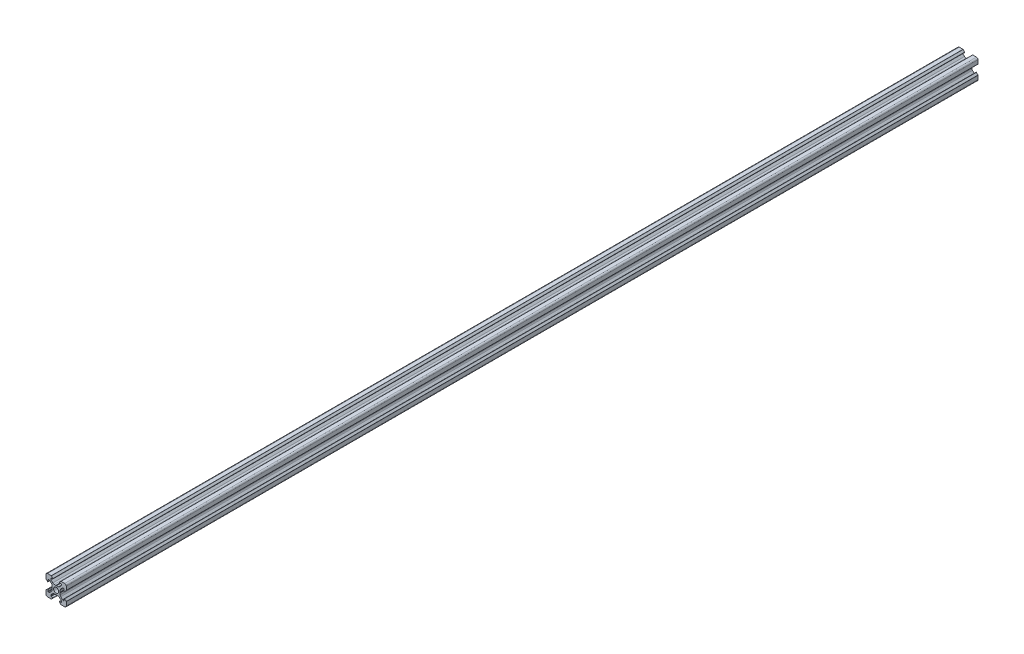
SolidWorks part; units mm, degrees
ref_plane "Спереди" through (0, 0, 0) normal (0, 0, 1) x (1, 0, 0)
ref_plane "Сверху" through (0, 0, 0) normal (0, 1, 0) x (1, 0, 0)
ref_plane "Справа" through (0, 0, 0) normal (1, 0, 0) x (0, 0, -1)
sketch "Model" plane through (0, 0, 0) normal (0, 0, 1) x (1, 0, 0)
  line L0 (18.9421, 33.3622) -> (18.9421, 34.9233)
  line L1 (18.3564, 36.3375) -> (16.6623, 38.0316)
  line L2 (15.9551, 38.3245) -> (15.1421, 38.3245)
  line L3 (14.9421, 38.1245) -> (14.9421, 36.3545)
  line L4 (13.0154, 37.6777) -> (14.5154, 36.1777)
  line L5 (12.9421, 37.8545) -> (12.9421, 41.5245)
  line L6 (18.2889, 42.9513) -> (19.7889, 41.4513)
  line L7 (22.7606, 36.9697) -> (22.9421, 36.8245)
  line L8 (23.1237, 36.9697) -> (22.9421, 36.8245)
  line L9 (23.2798, 37.0245) -> (24.8409, 37.0245)
  line L10 (26.2551, 37.6103) -> (27.9493, 39.3044)
  line L11 (28.2421, 40.0115) -> (28.2421, 40.8245)
  line L12 (28.0421, 41.0245) -> (26.2721, 41.0245)
  line L13 (27.5954, 42.9513) -> (26.0954, 41.4513)
  line L14 (27.7721, 43.0245) -> (31.4421, 43.0245)
  line L15 (32.9421, 37.8545) -> (32.9421, 41.5245)
  line L16 (32.8689, 37.6777) -> (31.3689, 36.1777)
  line L17 (30.9421, 38.1245) -> (30.9421, 36.3545)
  line L18 (29.9292, 38.3245) -> (30.7421, 38.3245)
  line L19 (27.5279, 36.3375) -> (29.222, 38.0316)
  line L20 (26.9421, 33.3622) -> (26.9421, 34.9233)
  line L21 (26.8874, 33.206) -> (26.7421, 33.0245)
  line L22 (26.8874, 32.843) -> (26.7421, 33.0245)
  line L23 (26.9421, 32.6868) -> (26.9421, 31.1257)
  line L24 (27.5279, 29.7115) -> (29.222, 28.0174)
  line L25 (29.9292, 27.7245) -> (30.7421, 27.7245)
  line L26 (30.9421, 27.9245) -> (30.9421, 29.6945)
  line L27 (32.8689, 28.3713) -> (31.3689, 29.8713)
  line L28 (32.9421, 28.1945) -> (32.9421, 24.5245)
  line L29 (27.7721, 23.0245) -> (31.4421, 23.0245)
  line L30 (27.5954, 23.0977) -> (26.0954, 24.5977)
  line L31 (28.0421, 25.0245) -> (26.2721, 25.0245)
  line L32 (28.2421, 26.0375) -> (28.2421, 25.2245)
  line L33 (26.2551, 28.4387) -> (27.9493, 26.7446)
  line L34 (23.2798, 29.0245) -> (24.8409, 29.0245)
  line L35 (23.1237, 29.0793) -> (22.9421, 29.2245)
  line L36 (22.7606, 29.0793) -> (22.9421, 29.2245)
  line L37 (19.6292, 28.4387) -> (17.935, 26.7446)
  line L38 (17.6421, 26.0375) -> (17.6421, 25.2245)
  line L39 (17.8421, 25.0245) -> (19.6121, 25.0245)
  line L40 (18.2889, 23.0977) -> (19.7889, 24.5977)
  line L41 (18.1121, 23.0245) -> (14.4421, 23.0245)
  line L42 (12.9421, 28.1945) -> (12.9421, 24.5245)
  line L43 (13.0154, 28.3713) -> (14.5154, 29.8713)
  line L44 (14.9421, 27.9245) -> (14.9421, 29.6945)
  line L45 (15.9551, 27.7245) -> (15.1421, 27.7245)
  line L46 (18.3564, 29.7115) -> (16.6623, 28.0174)
  line L47 (18.9421, 32.6868) -> (18.9421, 31.1257)
  line L48 (18.9969, 32.843) -> (19.1421, 33.0245)
  line L49 (18.9969, 33.206) -> (19.1421, 33.0245)
  line L50 (22.6045, 29.0245) -> (21.0434, 29.0245)
  line L51 (22.6045, 37.0245) -> (21.0434, 37.0245)
  line L52 (19.6292, 37.6103) -> (17.935, 39.3044)
  line L53 (17.6421, 40.0115) -> (17.6421, 40.8245)
  line L54 (17.8421, 41.0245) -> (19.6121, 41.0245)
  line L55 (18.1121, 43.0245) -> (14.4421, 43.0245)
  arc A0 (18.9421, 33.3622) -> (18.9969, 33.206) centre (19.1921, 33.3622) ccw
  arc A1 (18.9421, 34.9233) -> (18.3564, 36.3375) centre (16.9421, 34.9233) ccw
  arc A2 (16.6623, 38.0316) -> (15.9551, 38.3245) centre (15.9551, 37.3245) ccw
  arc A3 (15.1421, 38.3245) -> (14.9421, 38.1245) centre (15.1421, 38.1245) ccw
  arc A4 (14.5154, 36.1777) -> (14.9421, 36.3545) centre (14.6921, 36.3545) ccw
  arc A5 (12.9421, 37.8545) -> (13.0154, 37.6777) centre (13.1921, 37.8545) ccw
  arc A6 (14.4421, 43.0245) -> (12.9421, 41.5245) centre (14.4421, 41.5245) ccw
  arc A7 (18.2889, 42.9513) -> (18.1121, 43.0245) centre (18.1121, 42.7745) ccw
  arc A8 (19.6121, 41.0245) -> (19.7889, 41.4513) centre (19.6121, 41.2745) ccw
  arc A9 (17.8421, 41.0245) -> (17.6421, 40.8245) centre (17.8421, 40.8245) ccw
  arc A10 (17.6421, 40.0115) -> (17.935, 39.3044) centre (18.6421, 40.0115) ccw
  arc A11 (19.6292, 37.6103) -> (21.0434, 37.0245) centre (21.0434, 39.0245) ccw
  arc A12 (22.7606, 36.9697) -> (22.6045, 37.0245) centre (22.6045, 36.7745) ccw
  arc A13 (23.2798, 37.0245) -> (23.1237, 36.9697) centre (23.2798, 36.7745) ccw
  arc A14 (24.8409, 37.0245) -> (26.2551, 37.6103) centre (24.8409, 39.0245) ccw
  arc A15 (27.9493, 39.3044) -> (28.2421, 40.0115) centre (27.2421, 40.0115) ccw
  arc A16 (28.2421, 40.8245) -> (28.0421, 41.0245) centre (28.0421, 40.8245) ccw
  arc A17 (26.0954, 41.4513) -> (26.2721, 41.0245) centre (26.2721, 41.2745) ccw
  arc A18 (27.7721, 43.0245) -> (27.5954, 42.9513) centre (27.7721, 42.7745) ccw
  arc A19 (32.9421, 41.5245) -> (31.4421, 43.0245) centre (31.4421, 41.5245) ccw
  arc A20 (32.8689, 37.6777) -> (32.9421, 37.8545) centre (32.6921, 37.8545) ccw
  arc A21 (30.9421, 36.3545) -> (31.3689, 36.1777) centre (31.1921, 36.3545) ccw
  arc A22 (30.9421, 38.1245) -> (30.7421, 38.3245) centre (30.7421, 38.1245) ccw
  arc A23 (29.9292, 38.3245) -> (29.222, 38.0316) centre (29.9292, 37.3245) ccw
  arc A24 (27.5279, 36.3375) -> (26.9421, 34.9233) centre (28.9421, 34.9233) ccw
  arc A25 (26.8874, 33.206) -> (26.9421, 33.3622) centre (26.6921, 33.3622) ccw
  arc A26 (26.9421, 32.6868) -> (26.8874, 32.843) centre (26.6921, 32.6868) ccw
  arc A27 (26.9421, 31.1257) -> (27.5279, 29.7115) centre (28.9421, 31.1257) ccw
  arc A28 (29.222, 28.0174) -> (29.9292, 27.7245) centre (29.9292, 28.7245) ccw
  arc A29 (30.7421, 27.7245) -> (30.9421, 27.9245) centre (30.7421, 27.9245) ccw
  arc A30 (31.3689, 29.8713) -> (30.9421, 29.6945) centre (31.1921, 29.6945) ccw
  arc A31 (32.9421, 28.1945) -> (32.8689, 28.3713) centre (32.6921, 28.1945) ccw
  arc A32 (31.4421, 23.0245) -> (32.9421, 24.5245) centre (31.4421, 24.5245) ccw
  arc A33 (27.5954, 23.0977) -> (27.7721, 23.0245) centre (27.7721, 23.2745) ccw
  arc A34 (26.2721, 25.0245) -> (26.0954, 24.5977) centre (26.2721, 24.7745) ccw
  arc A35 (28.0421, 25.0245) -> (28.2421, 25.2245) centre (28.0421, 25.2245) ccw
  arc A36 (28.2421, 26.0375) -> (27.9493, 26.7446) centre (27.2421, 26.0375) ccw
  arc A37 (26.2551, 28.4387) -> (24.8409, 29.0245) centre (24.8409, 27.0245) ccw
  arc A38 (23.1237, 29.0793) -> (23.2798, 29.0245) centre (23.2798, 29.2745) ccw
  arc A39 (22.6045, 29.0245) -> (22.7606, 29.0793) centre (22.6045, 29.2745) ccw
  arc A40 (21.0434, 29.0245) -> (19.6292, 28.4387) centre (21.0434, 27.0245) ccw
  arc A41 (17.935, 26.7446) -> (17.6421, 26.0375) centre (18.6421, 26.0375) ccw
  arc A42 (17.6421, 25.2245) -> (17.8421, 25.0245) centre (17.8421, 25.2245) ccw
  arc A43 (19.7889, 24.5977) -> (19.6121, 25.0245) centre (19.6121, 24.7745) ccw
  arc A44 (18.1121, 23.0245) -> (18.2889, 23.0977) centre (18.1121, 23.2745) ccw
  arc A45 (12.9421, 24.5245) -> (14.4421, 23.0245) centre (14.4421, 24.5245) ccw
  arc A46 (13.0154, 28.3713) -> (12.9421, 28.1945) centre (13.1921, 28.1945) ccw
  arc A47 (14.9421, 29.6945) -> (14.5154, 29.8713) centre (14.6921, 29.6945) ccw
  arc A48 (14.9421, 27.9245) -> (15.1421, 27.7245) centre (15.1421, 27.9245) ccw
  arc A49 (15.9551, 27.7245) -> (16.6623, 28.0174) centre (15.9551, 28.7245) ccw
  arc A50 (18.3564, 29.7115) -> (18.9421, 31.1257) centre (16.9421, 31.1257) ccw
  arc A51 (18.9969, 32.843) -> (18.9421, 32.6868) centre (19.1921, 32.6868) ccw
  circle A52 centre (22.9421, 33.0245) radius 2.5
extrude "Бобышка-Вытянуть1" add sketch "Model" along normal blind 900
